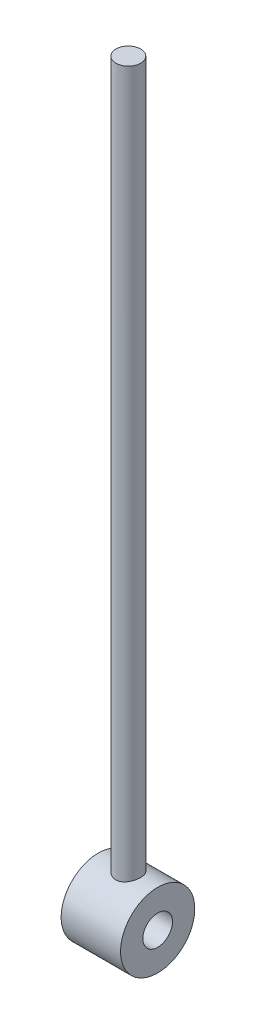
SolidWorks part; units mm, degrees
ref_plane "前视基准面" through (0, 0, 0) normal (0, 0, 1) x (1, 0, 0)
ref_plane "上视基准面" through (0, 0, 0) normal (0, 1, 0) x (1, 0, 0)
ref_plane "右视基准面" through (0, 0, 0) normal (1, 0, 0) x (0, 0, -1)
other "Configuration Table"
sketch "草图1" plane through (0, 0, 0) normal (1, 0, 0) x (0, 0, -1)
  circle A0 centre (0, 0) radius 7.5
  dimension "D1" = 15
extrude "凸台-拉伸1" add sketch "草图1" along normal blind 12
sketch "草图3" plane through (0, 0, 0) normal (0, 1, 0) x (1, 0, 0)
  circle A0 centre (6.0656, 0) radius 2.5
  dimension "D1" = 5
extrude "凸台-拉伸2" add sketch "草图3" along normal blind 150
sketch "草图2" plane through (12, 0, 0) normal (1, 0, 0) x (0, 0, -1)
  circle A0 centre (0, 0) radius 3
  dimension "D1" = 6
extrude "切除-拉伸1" cut sketch "草图2" against normal up to next
